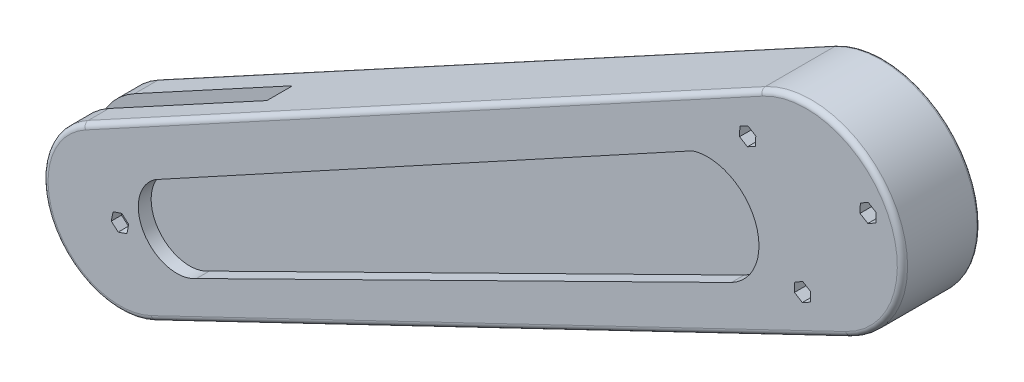
SolidWorks part; units mm, degrees
ref_plane "Front Plane" through (0, 0, 0) normal (0, 0, 1) x (1, 0, 0)
ref_plane "Top Plane" through (0, 0, 0) normal (0, 1, 0) x (1, 0, 0)
ref_plane "Right Plane" through (0, 0, 0) normal (1, 0, 0) x (0, 0, -1)
sketch "Sketch1" plane through (0, 0, 0) normal (0, 0, 1) x (1, 0, 0)
  line L3 (-281.4324, -110.2081) -> (-17.9006, 32.9518)
  line L4 (-254.127, -163.6138) -> (16.2311, -33.8053)
  arc A0 (16.2311, -33.8053) -> (-17.9006, 32.9518) centre (0, 0) ccw
  arc A1 (-281.4324, -110.2081) -> (-254.127, -163.6138) centre (-267.1119, -136.5695) ccw
  dimension "D1" = 75
  dimension "D2" = 60
  dimension "D3" = 300
extrude "Boss-Extrude1" add sketch "Sketch1" along normal blind 30
sketch "Sketch3" plane through (0, 0, 30) normal (0, 0, 1) x (1, 0, 0)
  line L2 (-4.4241, -25.1889) -> (-4.5358, -28.7672)
  line L3 (27.2927, 14.0337) -> (24.2497, 15.9196)
  line L4 (24.2497, 15.9196) -> (21.095, 14.2272)
  line L5 (21.095, 14.2272) -> (20.9833, 10.6489)
  line L6 (20.9833, 10.6489) -> (24.0263, 8.7631)
  line L7 (24.0263, 8.7631) -> (27.181, 10.4555)
  line L8 (27.181, 10.4555) -> (27.2927, 14.0337)
  line L9 (-4.5358, -28.7672) -> (-1.4928, -30.6531)
  line L10 (-1.4928, -30.6531) -> (1.6619, -28.9607)
  line L11 (1.6619, -28.9607) -> (1.7736, -25.3824)
  line L12 (1.7736, -25.3824) -> (-1.2694, -23.4965)
  line L13 (-1.2694, -23.4965) -> (-4.4241, -25.1889)
  line L14 (-19.6022, 16.4259) -> (-22.6452, 18.3117)
  line L15 (-22.6452, 18.3117) -> (-25.7999, 16.6193)
  line L16 (-25.7999, 16.6193) -> (-25.9116, 13.0411)
  line L17 (-25.9116, 13.0411) -> (-22.8686, 11.1552)
  line L18 (-22.8686, 11.1552) -> (-19.7139, 12.8476)
  line L19 (-19.7139, 12.8476) -> (-19.6022, 16.4259)
  circle A1 centre (24.138, 12.3413) radius 3.1004 construction
  point P28 (0, 0)
  dimension "D2" = 3.58
  dimension "D3" = 3
fillet "Fillet1" radius 2 4 edges at (33.389, 17.0712, 30) (-118.9479, -98.7095, 30) (-293.8231, -150.2264, 30) (-149.6665, -38.6281, 30)
fillet "Fillet2" radius 1 4 edges at (33.389, 17.0712, 0) (-118.9479, -98.7095, 0) (-293.8231, -150.2264, 0) (-149.6665, -38.6281, 0)
sketch "Sketch6" plane through (-17.9006, 32.9518, 0) normal (-0.4773, 0.8787, 0) x (0.8787, 0.4773, 0)
  line L0 (-329.9062, -1) -> (-329.9062, -28) construction
  line L1 (-329.9062, -10) -> (-229.9062, -10)
  line L2 (-329.9062, -10) -> (-329.9062, -20)
  line L3 (-329.9062, -20) -> (-229.9062, -20)
  line L4 (-229.9062, -10) -> (-229.9062, -20)
  line L5 (-299.9062, 0) -> (-328.9062, 0) construction
  dimension "D1" = 10
  dimension "D2" = 10
  dimension "D3" = 100
extrude "Cut-Extrude3" cut sketch "Sketch6" against normal blind 129
sketch "Sketch7" plane through (0, 0, 30) normal (0, 0, 1) x (1, 0, 0)
  line L1 (-263.7209, -135.4216) -> (-266.4105, -133.0589)
  line L2 (-266.4105, -133.0589) -> (-269.8015, -134.2067)
  line L3 (-269.8015, -134.2067) -> (-270.5029, -137.7174)
  line L4 (-270.5029, -137.7174) -> (-267.8133, -140.0801)
  line L5 (-267.8133, -140.0801) -> (-264.4223, -138.9322)
  line L6 (-264.4223, -138.9322) -> (-263.7209, -135.4216)
  circle A1 centre (-267.1119, -136.5695) radius 3.1004 construction
  dimension "D2" = 3.58
extrude "Cut-Extrude4" cut sketch "Sketch7" against normal blind 4
sketch "Sketch8" plane through (0, 0, 26) normal (0, 0, 1) x (1, 0, 0)
  circle A2 centre (-267.1119, -136.5695) radius 1.9
  dimension "D1" = 3.8
extrude "Cut-Extrude6" cut sketch "Sketch8" against normal blind 112
ref_plane "Plane1" through (0, 0, 15) normal (0, 0, 1) x (1, 0, 0)
mirror "Mirror1" about plane through (0, 0, 15) normal (0, 0, 1) of "Cut-Extrude4"
sketch "Sketch9" plane through (0, 0, 30) normal (0, 0, 1) x (1, 0, 0)
  line L1 (-20.6222, -10.7396) -> (0, 0) construction
  line L2 (-253.3734, -115.1475) -> (-44.1456, -0.8324)
  line L3 (-29.123, -37.7162) -> (-237.3244, -140.4793)
  arc A1 (-253.3734, -115.1475) -> (-237.3244, -140.4793) centre (-244.9871, -127.5842) ccw
  arc A2 (-29.123, -37.7162) -> (-44.1456, -0.8324) centre (-38.3609, -19.9776) ccw
  dimension "D1" = 40
  dimension "D2" = 30
extrude "Cut-Extrude7" cut sketch "Sketch9" against normal blind 5
mirror "Mirror2" about plane through (0, 0, 15) normal (0, 0, 1) of "Cut-Extrude7"
extrude "Cut-Extrude8" cut sketch "Sketch3" against normal blind 20
sketch "Sketch10" plane through (0, 0, 10) normal (0, 0, 1) x (1, 0, 0)
  circle A1 centre (24.0401, 12.2913) radius 1.75
  dimension "D1" = 3.5
extrude "Cut-Extrude9" cut sketch "Sketch10" against normal blind 70 and the other way blind 1
pattern_circular "CirPattern1" count 3 over 360 about axis through (0, 0, 0) along (0, 0, 1) of "Cut-Extrude9"
